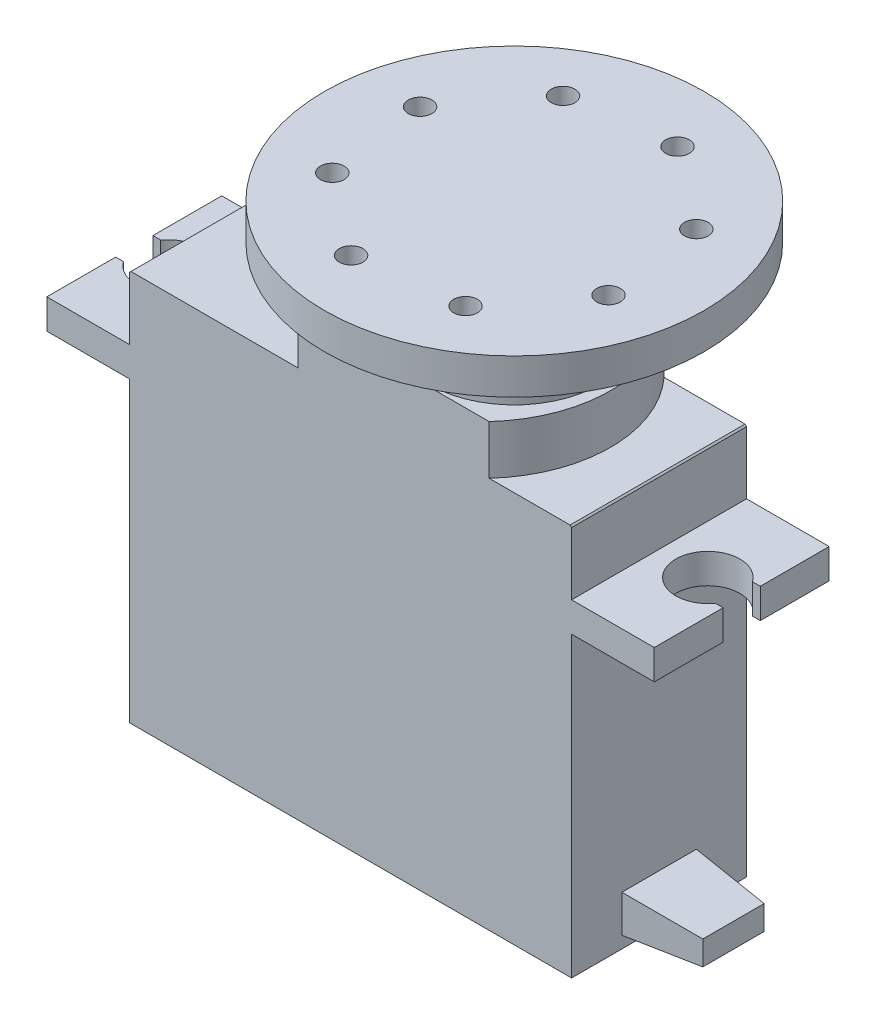
SolidWorks part; units mm, degrees
ref_plane "Front Plane" through (0, 0, 0) normal (0, 0, 1) x (1, 0, 0)
ref_plane "Top Plane" through (0, 0, 0) normal (0, 1, 0) x (1, 0, 0)
ref_plane "Right Plane" through (0, 0, 0) normal (1, 0, 0) x (0, 0, -1)
sketch "Sketch1" plane through (0, 0, 0) normal (0, 0, 1) x (1, 0, 0)
  line L0 (-20.4, 2) -> (-20.4, 0)
  line L1 (-20.4, 0) -> (-14.85, 0)
  line L2 (-14.85, 0) -> (-14.85, -20)
  line L3 (-14.85, -20) -> (14.85, -20)
  line L4 (0, -20) -> (0, 6.3) construction
  line L5 (20.4, 2) -> (14.85, 2)
  line L6 (14.85, 0) -> (14.85, -20)
  line L7 (20.4, 0) -> (14.85, 0)
  line L8 (20.4, 2) -> (20.4, 0)
  line L9 (-14.85, 2) -> (-14.85, 6.2)
  line L10 (-14.85, 6.2) -> (-14.75, 6.3)
  line L11 (-14.75, 6.3) -> (14.75, 6.3)
  line L12 (14.85, 6.2) -> (14.75, 6.3)
  line L13 (14.85, 2) -> (14.85, 6.2)
  line L14 (-14.85, 2) -> (-20.4, 2)
  point P16 (0, 6.3)
  dimension "D1" = 29.7
  dimension "D2" = 20
  dimension "D3" = 2
  dimension "D4" = 40.8
  dimension "D5" = 4.3
  dimension "D6" = 4.2
  dimension "D7" = 0.1
extrude "Boss-Extrude1" add sketch "Sketch1" along normal mid plane 11.75
sketch "Sketch2" plane through (0, 2, 0) normal (0, 1, 0) x (1, 0, 0)
  line L0 (-20.4, 1.25) -> (-19.8743, 1.25)
  line L1 (-20.4, -5.875) -> (-20.4, 5.875) construction
  line L2 (-20.4, -1.25) -> (-19.8743, -1.25)
  line L3 (-20.4, 1.25) -> (-20.4, -1.25)
  line L4 (-18.125, 0) -> (0, 0) construction
  line L5 (0, 0) -> (0, -6.0457) construction
  line L6 (20.4, 1.25) -> (20.4, -1.25)
  line L7 (20.4, -1.25) -> (19.8743, -1.25)
  line L8 (20.4, 1.25) -> (19.8743, 1.25)
  arc A0 (-19.8743, -1.25) -> (-19.8743, 1.25) centre (-18.125, 0) ccw
  arc A1 (19.8743, -1.25) -> (19.8743, 1.25) centre (18.125, 0) cw
  dimension "D3" = 2.15
  dimension "D4" = 36.25
  dimension "D2" = 2.5
extrude "Cut-Extrude1" cut sketch "Sketch2" against normal up to next
sketch "Sketch3" plane through (0, 2, 0) normal (0, 1, 0) x (1, 0, 0)
  line L0 (0, 0) -> (5.125, 0) construction
  circle A0 centre (5.125, 0) radius 3.9688
  arc A1 (19.8743, 1.25) -> (19.8743, -1.25) centre (18.125, 0) ccw construction
  dimension "D1" = 7.9375
  dimension "D2" = 13
extrude "Boss-Extrude2" add sketch "Sketch3" along normal blind 13
sketch "Sketch5" plane through (14.85, 0, 0) normal (1, 0, 0) x (0, 0, -1)
  line L0 (0, -16.7) -> (0, 0) construction
  line L1 (-2.5, -16.7) -> (2.5, -16.7)
  line L2 (-2.5, -16.7) -> (-2.5, -19.2)
  line L3 (-2.5, -19.2) -> (2.5, -19.2)
  line L4 (2.5, -16.7) -> (2.5, -19.2)
  line L5 (-5.875, -20) -> (5.875, -20) construction
  dimension "D1" = 5
  dimension "D2" = 2.5
  dimension "D3" = 0.8
extrude "Boss-Extrude4" add sketch "Sketch5" along normal blind 5 draft 5
sketch "Sketch6" plane through (0, 6.3, 0) normal (0, 1, 0) x (1, 0, 0)
  line L0 (0, 0) -> (2.8938, 0) construction
  line L1 (11.5938, 0) -> (9.0938, 0) construction
  circle A0 centre (2.8938, 0) radius 8.7
  circle A2 centre (5.125, 0) radius 3.9688 construction
  line M1 (14.75, 5.875) -> (-14.75, 5.875)
  line M3 (-14.75, -5.875) -> (14.75, -5.875)
  circle M5 centre (5.125, 0) radius 3.9688
  dimension "D1" = 17.4
  dimension "D2" = 2.5
extrude "Boss-Extrude5" add sketch "Sketch6" along normal blind 3.3 contours A0 M3 M1 M5
sketch "Sketch7" plane through (0, 9.6, 0) normal (0, 1, 0) x (1, 0, 0)
  circle A0 centre (5.125, 0) radius 5.75
  dimension "D1" = 11.5
extrude "Boss-Extrude6" add sketch "Sketch7" along normal blind 1.8
sketch "Sketch4" plane through (0, 15, 0) normal (0, 1, 0) x (1, 0, 0)
  circle A0 centre (5.125, 0) radius 12.75
  circle A1 centre (14.075, 0) radius 0.7937
  circle A2 centre (11.4536, 6.3286) radius 0.7937
  circle A3 centre (5.125, 8.95) radius 0.7938
  circle A4 centre (-3.825, 0) radius 0.7937
  circle A5 centre (-1.2036, -6.3286) radius 0.7937
  circle A6 centre (5.125, -8.95) radius 0.7938
  circle A7 centre (11.4536, -6.3286) radius 0.7938
  circle A8 centre (-1.2036, 6.3286) radius 0.7937
  point P23 (5.125, 0)
  dimension "D5" = 1.5875
  dimension "D2" = 17.9
  dimension "D3" = 25.5
  dimension "D1" = 8
extrude "Boss-Extrude3" add sketch "Sketch4" along normal blind 2.4 separate body
move or copy body "Body-Move/Copy1" bodies to move or copy 104 copy no rotation origin (5.125, 0, 0) rotation axis (0, 1, 0) rotation angle 30
